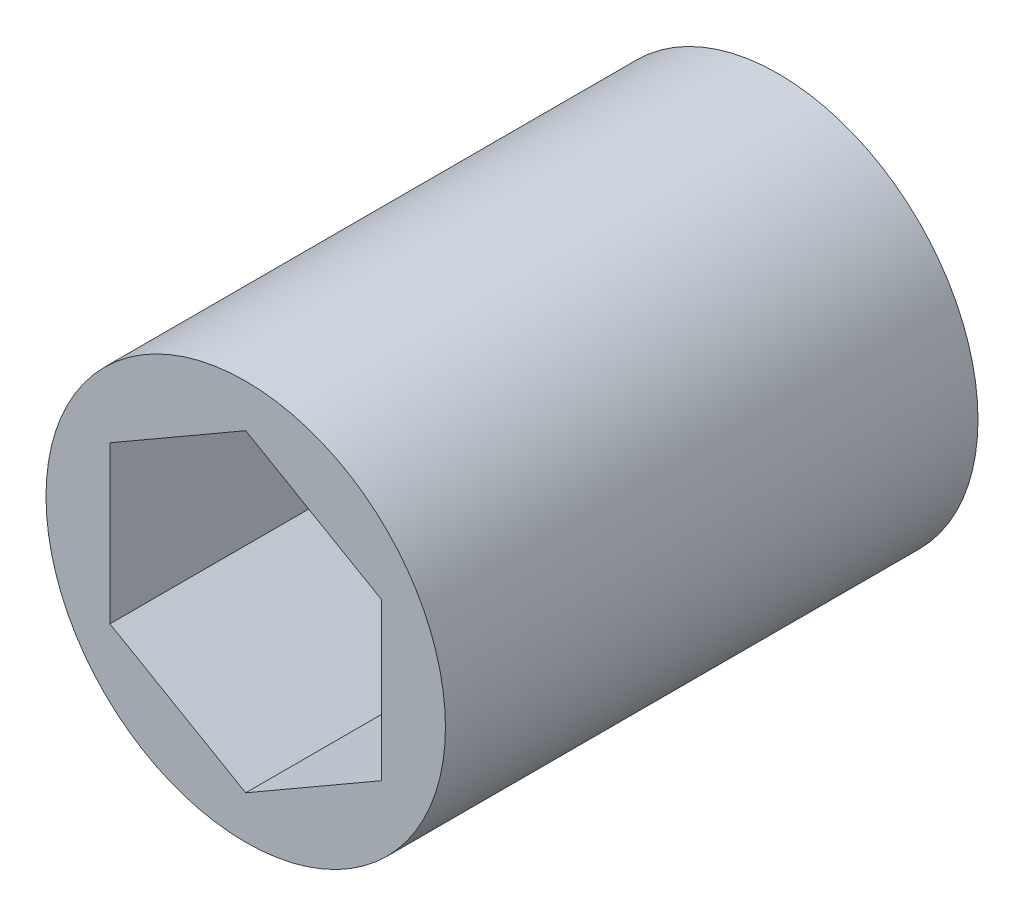
SolidWorks part; units mm, degrees
material "PET"
ref_plane "Front Plane" through (0, 0, 0) normal (0, 0, 1) x (1, 0, 0)
ref_plane "Top Plane" through (0, 0, 0) normal (0, 1, 0) x (1, 0, 0)
ref_plane "Right Plane" through (0, 0, 0) normal (1, 0, 0) x (0, 0, -1)
sketch "Sketch1" plane through (0, 0, 0) normal (0, 0, 1) x (1, 0, 0)
  line L1 (0, 7.479) -> (-6.477, 3.7395)
  line L2 (-6.477, 3.7395) -> (-6.477, -3.7395)
  line L3 (-6.477, -3.7395) -> (0, -7.479)
  line L4 (0, -7.479) -> (6.477, -3.7395)
  line L5 (6.477, -3.7395) -> (6.477, 3.7395)
  line L6 (6.477, 3.7395) -> (0, 7.479)
  circle A0 centre (0, 0) radius 9.525
  circle A1 centre (0, 0) radius 6.477 construction
  dimension "D1" = 19.05
  dimension "D2" = 12.954
extrude "Boss-Extrude1" add sketch "Sketch1" along normal mid plane 25.4
